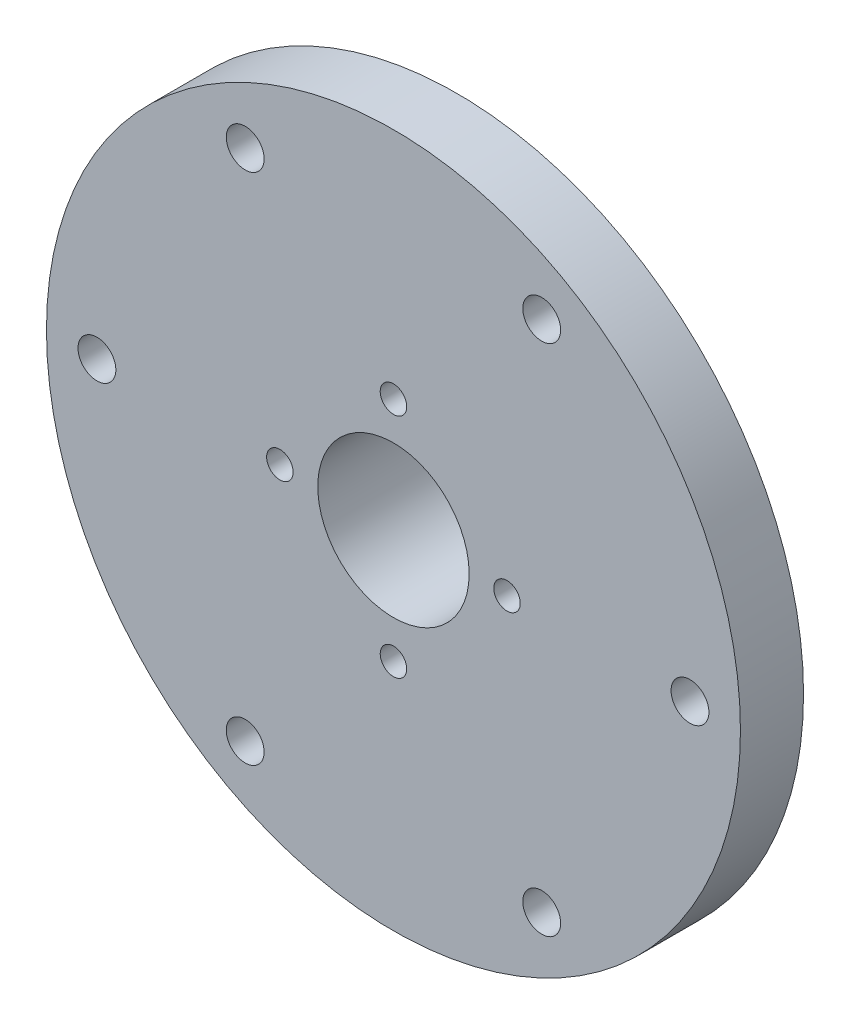
SolidWorks part; units mm, degrees
ref_plane "Front" through (0, 0, 0) normal (0, 0, 1) x (1, 0, 0)
ref_plane "Top" through (0, 0, 0) normal (0, 1, 0) x (1, 0, 0)
ref_plane "Right" through (0, 0, 0) normal (1, 0, 0) x (0, 0, -1)
sketch "草图1" plane through (0, 0, 0) normal (0, 0, 1) x (1, 0, 0)
  circle A0 centre (0, 0) radius 12
  circle A1 centre (0, 0) radius 55
  circle A4 centre (47, 0) radius 3
  circle A7 centre (23.5, -40.7032) radius 3
  circle A8 centre (-23.5, -40.7032) radius 3
  circle A9 centre (-47, 0) radius 3
  circle A10 centre (-23.5, 40.7032) radius 3
  circle A11 centre (23.5, 40.7032) radius 3
  point P21 (0, 0)
  point P28 (0, 0)
  dimension "D1" = 6
extrude "凸台-拉伸1" add sketch "草图1" along normal blind 20
sketch "草图2" plane through (0, 0, 0) normal (0, 0, 1) x (1, 0, 0)
  circle A0 centre (0, 0) radius 25
extrude "切除-拉伸1" cut sketch "草图2" along normal blind 10 flip side to cut
sketch "草图4" plane through (0, 0, 0) normal (0, 0, 1) x (1, 0, 0)
  circle A1 centre (-47, 0) radius 5
  circle A2 centre (-23.5, 40.7032) radius 5
  circle A3 centre (23.5, 40.7032) radius 5
  circle A4 centre (47, 0) radius 5
  circle A5 centre (23.5, -40.7032) radius 5
  circle A6 centre (-23.5, -40.7032) radius 5
  point P19 (0, 0)
  dimension "D1" = 6
extrude "切除-拉伸2" cut sketch "草图4" along normal blind 15
sketch "草图5" plane through (0, 0, 0) normal (0, 0, -1) x (-1, 0, 0)
  line L0 (0, 0) -> (0, 18)
  line L1 (0, 0) -> (18, 0)
  line L2 (0, 0) -> (0, -18)
  line L3 (0, 0) -> (-18, 0)
hole_wizard "M5 螺纹孔的螺纹孔钻头1" positions "草图6" profile "草图7" hole size "M5" standard "GB" end condition through all
sketch "草图6" plane through (0, 0, 0) normal (0, 0, -1) x (-1, 0, 0)
  point P0 (0, 18)
  point P3 (18, 0)
  point P6 (0, -18)
  point P9 (-18, 0)
sketch "草图7" plane through (0, 18, 0) normal (1, 0, 0) x (0, 1, 0)
  line L0 (0, 0) -> (0, 20)
  line L1 (0, 20) -> (2.1, 20)
  line L2 (2.1, 20) -> (2.1, 0)
  line L5 (2.1, 0) -> (0, 0)
  line L11 (0, -6.35) -> (0, 107.95) construction
  dimension "通孔孔直径" = 4.2
  dimension "通孔孔深度" = 20
